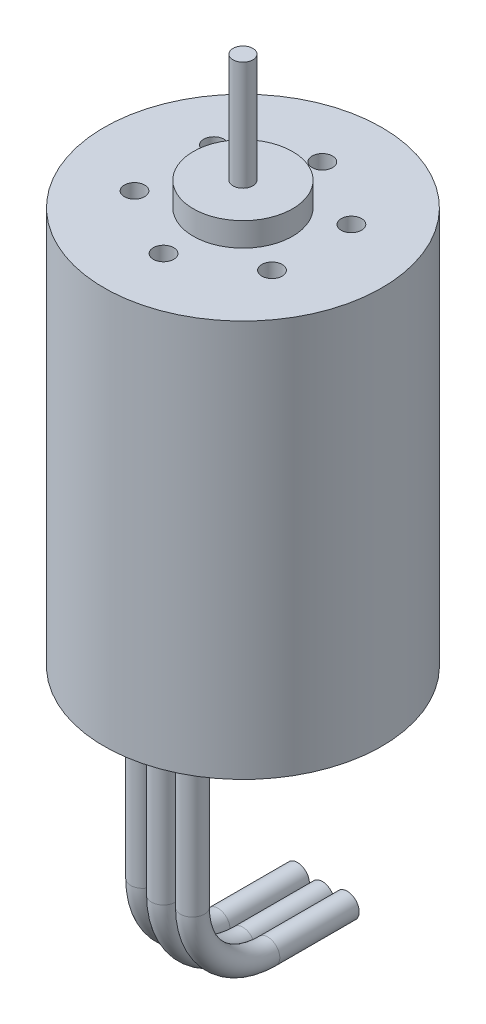
SolidWorks part; units mm, degrees
ref_plane "Front Plane" through (0, 0, 0) normal (0, 0, 1) x (1, 0, 0)
ref_plane "Top Plane" through (0, 0, 0) normal (0, 1, 0) x (1, 0, 0)
ref_plane "Right Plane" through (0, 0, 0) normal (1, 0, 0) x (0, 0, -1)
sketch "Sketch1" plane through (0, 0, 0) normal (0, 0, 1) x (1, 0, 0)
  line L0 (0, 0) -> (0, 55.8) construction
  line L1 (0, 55.8) -> (1, 55.8)
  line L2 (1, 55.8) -> (1, 44.8)
  line L3 (1, 44.8) -> (5, 44.8)
  line L4 (14, 42.4) -> (14, 2.4)
  line L5 (0, 0) -> (5, 0)
  line L6 (0, 0) -> (0, 55.8)
  line L7 (5, 0) -> (5, 2.4)
  line L8 (5, 2.4) -> (14, 2.4)
  line L9 (5, 44.8) -> (5, 42.4)
  line L10 (5, 42.4) -> (14, 42.4)
  dimension "D1" = 2.4
  dimension "D2" = 28
  dimension "D3" = 2
  dimension "D4" = 40
  dimension "D5" = 2.4
  dimension "D6" = 11
  dimension "D7" = 5
  dimension "D8" = 5
revolve "Revolve1" add sketch "Sketch1" angle 360 about L0
hole_wizard "M2.5x0.45 Tapped Hole1" positions "Sketch3" profile "Sketch2" tap size "M2.5x0.45" standard "ANSI Metric"
sketch "Sketch3" plane through (0, 42.4, 0) normal (0, 1, 0) x (1, 0, 0)
  line L1 (0, 0) -> (0, 8) construction
  point P0 (0, 8)
  dimension "D1" = 8
sketch "Sketch2" plane through (0, 42.4, -8) normal (1, 0, 0) x (0, 0, 1)
  line L0 (0, 0) -> (0, 4.6159)
  line L1 (0, 4.6159) -> (1.025, 4)
  line L2 (1.025, 4) -> (1.025, 0)
  line L5 (1.025, 0) -> (0, 0)
  line L10 (0, 4.6159) -> (-1.025, 4) construction
  line L11 (0, -6.35) -> (0, 107.95) construction
  dimension "Tap Drill Dia." = 2.05
  dimension "Tap Drill Depth" = 4
  dimension "Drill Angle" = 118
cosmetic thread "Hole Thread1" parameters "D1"=4, "D2"=2.5
pattern_circular "CirPattern1" count 6 over 360 about axis through (0, 0, 0) along (0, 1, 0) of "M2.5x0.45 Tapped Hole1"
sketch "Sketch4" plane through (0, 2.4, 0) normal (0, -1, 0) x (-1, 0, 0)
  line L0 (2.5078, -7.5968) -> (0, -8) construction
  line L1 (0, -8) -> (-2.5078, -7.5968) construction
  line L2 (-2.5078, -7.5968) -> (0, 0) construction
  line L3 (0, 0) -> (0, -8) construction
  line L4 (2.5078, -7.5968) -> (0, 0) construction
  circle A0 centre (-2.5078, -7.5968) radius 1.2065
  circle A1 centre (0, -8) radius 1.2065
  circle A2 centre (2.5078, -7.5968) radius 1.2065
  point P0 (-2.5078, -7.5968)
  point P1 (0, -8)
  point P2 (2.5078, -7.5968)
  dimension "D1" = 2.413
  dimension "D2" = 2.54
  dimension "D3" = 2.54
  dimension "D4" = 8
sketch "Sketch5" plane through (0, 0, 0) normal (1, 0, 0) x (0, 0, -1)
  line L0 (-8, 2.4) -> (-8, -13.6)
  line L1 (0, -21.6) -> (8, -21.6)
  arc A0 (-8, -13.6) -> (0, -21.6) centre (0, -13.6) ccw
  dimension "D2" = 8
  dimension "D1" = 24
  dimension "D3" = 8
sweep "Sweep1" add profiles "Sketch4" path "Sketch5"
